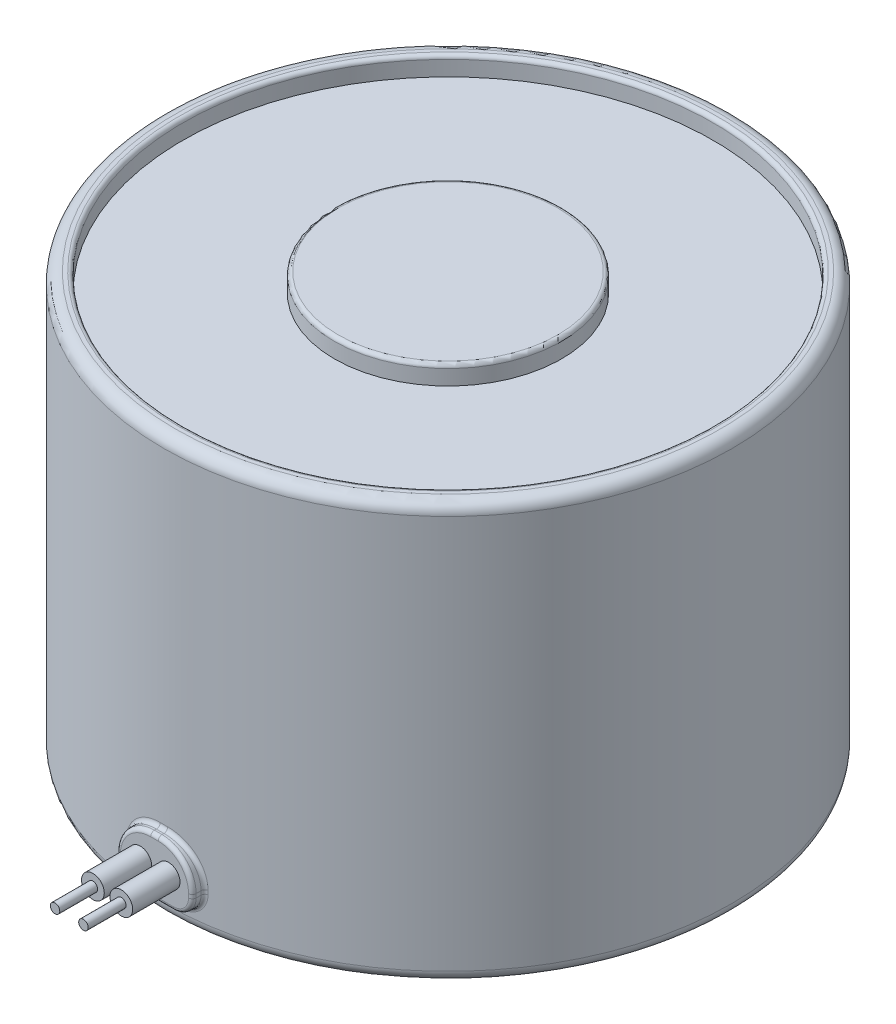
SolidWorks part; units mm, degrees
ref_plane "Front" through (0, 0, 0) normal (0, 0, 1) x (1, 0, 0)
ref_plane "Top" through (0, 0, 0) normal (0, 1, 0) x (1, 0, 0)
ref_plane "Right" through (0, 0, 0) normal (1, 0, 0) x (0, 0, -1)
sketch "Sketch11" plane through (0, 0, 0) normal (0, 1, 0) x (1, 0, 0)
  circle A0 centre (0, 0) radius 8 construction
  circle A1 centre (0, 0) radius 10 construction
  circle A2 centre (0, 0) radius 12.5 construction
  circle A3 centre (0, 0) radius 15 construction
  circle A4 centre (0, 0) radius 17 construction
  dimension "D1" = 16
  dimension "D2" = 20
  dimension "D3" = 25
  dimension "D4" = 30
  dimension "D5" = 34
sketch "Sketch1" plane through (0, 0, 0) normal (0, 1, 0) x (1, 0, 0)
  circle A0 centre (0, 0) radius 15
  circle A3 centre (0, 0) radius 8 construction
  circle A4 centre (0, 0) radius 10 construction
  circle A5 centre (0, 0) radius 12.5 construction
  circle A6 centre (0, 0) radius 15 construction
  circle A7 centre (0, 0) radius 17 construction
extrude "Boss-Extrude1" add sketch "Sketch1" along normal blind 22
ref_plane "Plane1" through (0, 0, 15) normal (0, 0, 1) x (1, 0, 0)
sketch "Sketch12" plane through (0, 22, 0) normal (0, 1, 0) x (1, 0, 0)
  circle A0 centre (0, 0) radius 2.5 construction
  circle A1 centre (0, 0) radius 4 construction
  circle A2 centre (0, 0) radius 5 construction
  circle A3 centre (0, 0) radius 6 construction
  circle A4 centre (0, 0) radius 8 construction
  dimension "D1" = 5
  dimension "D2" = 8
  dimension "D3" = 10
  dimension "D4" = 12
  dimension "D5" = 16
sketch "Sketch13" plane through (0, 0, 0) normal (0, 1, 0) x (1, 0, 0)
  circle A0 centre (0, 0) radius 16 construction
  circle A1 centre (0, 0) radius 14 construction
  circle A2 centre (0, 0) radius 11.5 construction
  circle A3 centre (0, 0) radius 9 construction
  circle A4 centre (0, 0) radius 7 construction
  dimension "D1" = 32
  dimension "D2" = 28
  dimension "D3" = 23
  dimension "D4" = 18
  dimension "D5" = 14
sketch "Sketch2" plane through (0, 22, 0) normal (0, 1, 0) x (1, 0, 0)
  circle A0 centre (0, 0) radius 14
  circle A1 centre (0, 0) radius 6
  circle A2 centre (0, 0) radius 2.5 construction
  circle A3 centre (0, 0) radius 4 construction
  circle A4 centre (0, 0) radius 5 construction
  circle A5 centre (0, 0) radius 6 construction
  circle A6 centre (0, 0) radius 8 construction
  circle A11 centre (0, 0) radius 16 construction
  circle A12 centre (0, 0) radius 14 construction
  circle A13 centre (0, 0) radius 11.5 construction
  circle A14 centre (0, 0) radius 9 construction
  circle A15 centre (0, 0) radius 7 construction
extrude "Cut-Extrude1" cut sketch "Sketch2" against normal blind 1
hole_wizard "M4 Tapped Hole1" positions "Sketch5" profile "Sketch7" tap size "M4" standard "ISO"
sketch "Sketch5" plane through (0, 0, 0) normal (0, -1, 0) x (-1, 0, 0)
  point P0 (0, 0)
sketch "Sketch7" plane through (0, 0, 0) normal (1, 0, 0) x (0, 0, -1)
  line L0 (0, 0) -> (0, 6.9526)
  line L1 (0, 6.9526) -> (1.65, 6)
  line L2 (1.65, 6) -> (1.65, 0.6)
  line L3 (1.65, 0.6) -> (2.25, 0)
  line L5 (2.25, 0) -> (0, 0)
  line L6 (-1.65, 0.6) -> (-2.25, 0) construction
  line L10 (0, 6.9526) -> (-1.65, 6) construction
  line L11 (0, -6.35) -> (0, 107.95) construction
  dimension "Tap Drill Dia." = 3.3
  dimension "Tap Drill Depth" = 6
  dimension "Near C'Sink Dia." = 4.5
  dimension "Near C'Sink Angle" = 90
  dimension "Drill Angle" = 120
cosmetic thread "Hole Thread1" parameters "D1"=6, "D2"=4
sketch "Sketch8" plane through (0, 0, 15) normal (0, 0, 1) x (1, 0, 0)
  line L0 (0, 0) -> (0, 22) construction
  line L1 (15, 22) -> (-15, 22) construction
  line L3 (-0.2, 4) -> (0.2, 4)
  line L4 (-2, 2.2) -> (-2, 2)
  line L5 (-1, 1) -> (1, 1)
  line L6 (2, 2.2) -> (2, 2)
  line L7 (-2, 4) -> (2, 1) construction
  line L8 (-2, 1) -> (2, 4) construction
  arc A0 (1, 1) -> (2, 2) centre (1, 2) ccw
  arc A1 (-2, 2) -> (-1, 1) centre (-1, 2) ccw
  arc A2 (0.2, 4) -> (2, 2.2) centre (0.2, 2.2) cw
  arc A3 (-0.2, 4) -> (-2, 2.2) centre (-0.2, 2.2) ccw
  point P6 (0, 2.5)
  dimension "D4" = 1.8
  dimension "D5" = 1
  dimension "D6" = 1.8
  dimension "D1" = 3
  dimension "D2" = 4
  dimension "D3" = 1
extrude "Boss-Extrude2" add sketch "Sketch8" along normal blind 0.5 and the other way up to surface other way up to face at (0, 22, 15)
sketch "Sketch9" plane through (0, 0, 15) normal (0, 0, 1) x (1, 0, 0)
  line L0 (0, 4) -> (0, 1) construction
  line L1 (0.2, 4) -> (-0.2, 4) construction
  line L2 (-1, 1) -> (1, 1) construction
  line L3 (-1.9748, 2.5) -> (1.9748, 2.5) construction
  arc A0 (-0.2, 4) -> (-2, 2.2) centre (-0.2, 2.2) ccw construction
  arc A1 (2, 2.2) -> (0.2, 4) centre (0.2, 2.2) ccw construction
  circle A2 centre (-0.75, 2.5) radius 0.6
  circle A3 centre (0.75, 2.5) radius 0.6
  dimension "D1" = 1.2
  dimension "D2" = 1.5
extrude "Boss-Extrude3" add sketch "Sketch9" along normal blind 3
sketch "Sketch10" plane through (0, 0, 15) normal (0, 0, 1) x (1, 0, 0)
  line L0 (0, 4) -> (0, 1) construction
  line L1 (0.2, 4) -> (-0.2, 4) construction
  line L2 (-1, 1) -> (1, 1) construction
  circle A0 centre (-0.75, 2.5) radius 0.25
  circle A1 centre (0.75, 2.5) radius 0.25
  dimension "D1" = 0.5
extrude "Boss-Extrude4" add sketch "Sketch10" along normal blind 5
fillet "Fillet1" radius 0.6 2 edges at (0, 0, 15) (0, 22, 15)
fillet "Fillet2" radius 0.2 16 edges at (0, 4, 15) (1.6103, 3.3186, 14.9133) (2, 2.1, 14.8661) (1.6258, 1.22, 14.9116) (0, 1, 15) (-1.7838, 1.379, 14.8936) (-2, 2.1, 14.8661) (0, 4, 15.5) (1.4728, 3.4728, 15.5) (2, 2.1, 15.5) (1.7071, 1.2929, 15.5) (0, 1, 15.5) (-1.7071, 1.2929, 15.5) (-2, 2.1, 15.5) (-1.3205, 3.6087, 14.9418) (-1.4728, 3.4728, 15.5)
fillet "Fillet3" radius 0.2 1 edges at (0, 22, 6)
fillet "Fillet4" radius 0.2 1 edges at (0, 22, 14)
